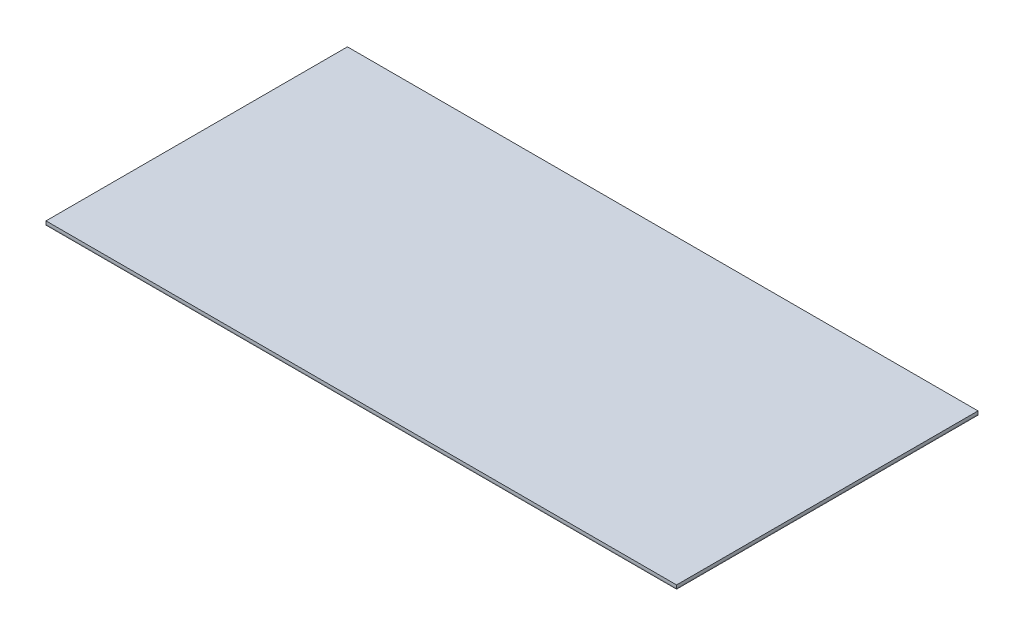
SolidWorks part; units mm, degrees
ref_plane "Alzado" through (0, 0, 0) normal (0, 0, 1) x (1, 0, 0)
ref_plane "Planta" through (0, 0, 0) normal (0, 1, 0) x (1, 0, 0)
ref_plane "Vista lateral" through (0, 0, 0) normal (1, 0, 0) x (0, 0, -1)
sketch "Croquis1" plane through (0, 0, 0) normal (0, 1, 0) x (1, 0, 0)
  line L1 (1025, -490) -> (-1025, -490)
  line L2 (1025, -490) -> (1025, 490)
  line L3 (1025, 490) -> (-1025, 490)
  line L4 (-1025, -490) -> (-1025, 490)
  line L5 (1025, -490) -> (-1025, 490) construction
  line L6 (1025, 490) -> (-1025, -490) construction
  point P0 (0, 0)
  dimension "D1" = 2050
  dimension "D2" = 980
extrude "Extruir1" add sketch "Croquis1" along normal blind 10
sketch "Croquis2" plane through (0, 0, 0) normal (0, -1, 0) x (1, 0, 0)
  line L4 (-1025, 490) -> (-1025, -490)
  line L5 (-1025, -490) -> (1025, -490)
  line L6 (1025, -490) -> (1025, 490)
  line L7 (1025, 490) -> (-1025, 490)
  line L8 (-1025, 490) -> (-1025, -490)
  line L9 (-1025, -490) -> (1025, -490)
  line L10 (1025, -490) -> (1025, 490)
  line L11 (1025, 490) -> (-1025, 490)
  dimension "D1" = 0
extrude "Extruir2" add sketch "Croquis2" along normal blind 2 separate body
